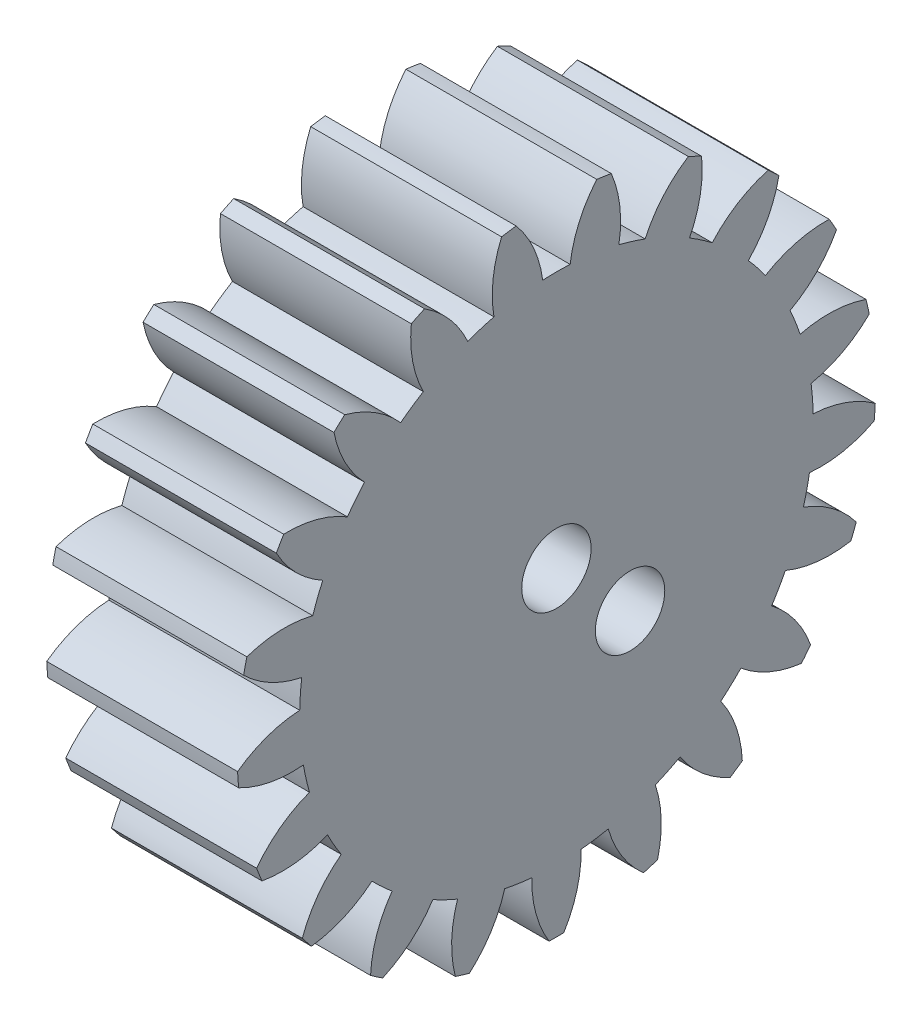
SolidWorks part; units mm, degrees
ref_plane "Plane1" through (0, 0, 0) normal (0, 0, 1) x (1, 0, 0)
ref_plane "Plane2" through (0, 0, 0) normal (0, 1, 0) x (1, 0, 0)
ref_plane "Plane3" through (0, 0, 0) normal (1, 0, 0) x (0, 0, -1)
sketch "HoldingSke" plane through (0, 0, 0) normal (0, 1, 0) x (1, 0, 0)
  line L0 (0, 0) -> (1.167, -0.448)
  line L1 (-15, 0) -> (100, 0) construction
  line L2 (0, 0) -> (-2.1039, 2.3779)
  line L3 (0, 0) -> (-11.863, 4.5341)
  line L4 (0, 0) -> (8.0624, 3.0949)
  line L5 (0, 0) -> (-46.8476, -17.4728)
  line L6 (0, 0) -> (-4.5593, -3.0762)
  line L7 (-2.1039, 2.3779) -> (8.6586, 51.2059)
  line L8 (-76.2, 54.61) -> (-75.9, 54.61)
  line L9 (-71.009, 38.7566) -> (-53.1078, 45.2721)
  line L10 (-76.2, 71.12) -> (104.1128, 71.12)
  line L11 (0, 0) -> (-5.5, 0)
  line L12 (-76.2, 101.6) -> (-76.17, 101.6)
  line L13 (24.9733, 27.94) -> (52.9518, 28.4284)
  line L14 (24.9733, 27.94) -> (24.9743, 27.94)
  line L15 (24.9733, 27.94) -> (100.4006, 29.5858)
  line L16 (-63.627, -0.8) -> (-12.827, -0.8)
  circle A0 centre (0, 0) radius 1
  circle A1 centre (0, 0) radius 7.399
  circle A2 centre (0, 0) radius 37.5
  circle A3 centre (0, 0) radius 1
  dimension "MHD" = 14.798
  dimension "Hub_dia" = 75
  dimension "Bore" = 2
  dimension "MBD" = 2
  dimension "Num_teeth" = 21
  dimension "Pitch" = 1.25
  dimension "Overall_len" = 50
  dimension "Show_teeth" = 21
  dimension "Thickness" = 5.5
  dimension "OAL" = 50.0001
  dimension "T_dim" = 0.3
  dimension "Ap" = 20
  dimension "H" = 19.05
  dimension "Pitch_radius" = 180.3128
  dimension "Width" = 5.5
  dimension "Backlash" = 0.03
  dimension "Addendum_fac" = 1
  dimension "Dedendum_fac" = 1.25
  dimension "Clearance_fac" = 0.25
  dimension "Dedendum_add" = 0.001
  dimension "Module" = 0.8
sketch "BasProSke" plane through (0, 0, 0) normal (0, 1, 0) x (1, 0, 0)
  line L0 (-10, 0) -> (60, 0) construction
  line L1 (0, 0) -> (0, 9.2)
  line L2 (0, 0) -> (5.5, 0)
  line L3 (5.5, 0) -> (5.5, 9.2)
  line L4 (5.5, 9.2) -> (0, 9.2)
  dimension "Thickness" = 5.5
  dimension "Diameter" = 18.4
revolve "Base-Revolve" add sketch "BasProSke" angle 360 about L0
sketch "TooCutSke" plane through (0, 0, 0) normal (1, 0, 0) x (0, 0, -1)
  line L1 (0, 0) -> (0, 107) construction
  line L2 (0, 0) -> (-0.6802, 8.3724) construction
  line L3 (0, 0) -> (-2.498, 16.5734) construction
  line L4 (-0.6802, 8.3724) -> (-1.249, 8.2867) construction
  arc A0 (0.3956, 7.3884) -> (-0.3956, 7.3884) centre (0, 0) ccw
  arc A1 (1.1812, 9.1495) -> (-1.1812, 9.1495) centre (0, 0) ccw
  circle A2 centre (0, 0) radius 8.4 construction
  circle A3 centre (0, 0) radius 7.8934 construction
  arc A4 (-0.3956, 7.3884) -> (-1.1812, 9.1495) centre (-3.7278, 6.9577) ccw
  arc A5 (1.1812, 9.1495) -> (0.3956, 7.3884) centre (3.7278, 6.9577) ccw
  dimension "Root_dia" = 14.798
  dimension "Overcut_dia" = 18.4508
  dimension "Pitch_dia" = 16.8
  dimension "Base_dia" = 15.7868
  dimension "Flank_rad" = 3.36
  dimension "Half_ang" = 8.571
  dimension "Half_CT" = 0.5752
extrude "ToothCut" cut sketch "TooCutSke" along normal through all
fillet "Breaks" [suppressed] radius 0.016
fillet "RootFillets" [suppressed] radius 0.201
pattern_circular "TeethCuts" count 21 every 17.143 about axis through (-10, 0, 0) along (1, 0, 0) of "ToothCut", "RootFillets", "Breaks"
sketch "HubNeaOneSke" plane through (0, 0, 0) normal (-1, 0, 0) x (0, 0, 1)
  circle A0 centre (0, 0) radius 7.399
  dimension "Diameter" = 14.798
extrude "HubNearOne" [suppressed] add sketch "HubNeaOneSke" along normal blind 44.5001
sketch "HubNeaBotSke" plane through (0, 0, 0) normal (-1, 0, 0) x (0, 0, 1)
  circle A0 centre (0, 0) radius 7.399
  dimension "Diameter" = 14.798
extrude "HubNearBoth" [suppressed] add sketch "HubNeaBotSke" along normal blind 22.25
ref_plane "FarPln" through (5.5, 0, 0) normal (1, 0, 0) x (0, 0, -1)
sketch "HubFarSke" plane through (5.5, 0, 0) normal (1, 0, 0) x (0, 0, -1)
  circle A0 centre (0, 0) radius 7.399
  dimension "Diameter" = 14.798
extrude "HubFar" [suppressed] add sketch "HubFarSke" along normal blind 22.25
sketch "BorSke" plane through (0, 0, 0) normal (1, 0, 0) x (0, 0, -1)
  circle A0 centre (0, 0) radius 1
  dimension "Diameter" = 2
extrude "Bore" cut sketch "BorSke" along normal mid plane 100.0001
sketch "KeySke" plane through (0, 0, 0) normal (1, 0, 0) x (0, 0, -1)
  line L0 (-0.4, 0) -> (-0.4, 1.3)
  line L1 (-0.4, 1.3) -> (0.4, 1.3)
  line L2 (0.4, 1.3) -> (0.4, 0)
  line L3 (0, 0) -> (0, 34) construction
  line L4 (-0.4, 0) -> (0.4, 0)
  dimension "Offset" = 1.3
  dimension "Width" = 0.8
extrude "Keyway" [suppressed] cut sketch "KeySke" along normal mid plane 100.0001
pattern_circular "Keyway2" [suppressed] count 2 every 90 about axis through (-10, 0, 0) along (1, 0, 0)
sketch "Sketch1" plane through (5.5, 0, 0) normal (1, 0, 0) x (0, 0, -1)
  line L0 (0, 0) -> (2.1213, -2.1213) construction
  circle A0 centre (2.1213, -2.1213) radius 1
  dimension "D1" = 3
extrude "Cut-Extrude1" cut sketch "Sketch1" against normal blind 5.5 contours A0
equation "' \"Module@HoldingSke\" = 6.35"
equation "' \"Num_teeth@HoldingSke\" = 12"
equation "' \"Ap@HoldingSke\" =  20"
equation "' \"Ap@HoldingSke\" = 20"
equation "' \"Width@HoldingSke\" = 0.5 * 25.4"
equation "' \"Hub_dia@HoldingSke\"= 1 * 25.4"
equation "' \"Hub_dia@HoldingSke\" = 1 * 25.4"
equation "' \"Overall_len@HoldingSke\" = 1.0 * 25.4"
equation "' \"Bore@HoldingSke\" = 0.75 * 25.4"
equation "' \"T_dim@HoldingSke\" = 0.1 * 25.4"
equation "' \"Width@KeySke\" = 0.25 * 25.4"
equation "' \"Show_teeth@HoldingSke\" = 13"
equation "' \"Backlash@HoldingSke\" = 0.009 * 25.4"
equation "' \"Addendum_fac@HoldingSke\" = 1.0"
equation "' \"Dedendum_fac@HoldingSke\" = 1.25"
equation "' \"Dedendum_add@HoldingSke\" = 0.00005 * 25.4"
equation "' \"Clearance_fac@HoldingSke\" = 0.25"
equation "\"Pitch@HoldingSke\" = 1 / \"Module@HoldingSke\""
equation "\"Overcut_dia@TooCutSke\" = (\"Num_teeth@HoldingSke\" + 2 * \"Addendum_fac@HoldingSke\") / \"Pitch@HoldingSke\" + 0.002 * 25.4"
equation "\"Pitch_dia@TooCutSke\" = \"Num_teeth@HoldingSke\" / \"Pitch@HoldingSke\""
equation "\"Base_dia@TooCutSke\" = \"Num_teeth@HoldingSke\" / \"Pitch@HoldingSke\" * cos((\"Ap@HoldingSke\"  * 3.14159265 / 180))"
equation "\"Root_dia@TooCutSke\" = (\"Num_teeth@HoldingSke\" + 2) / \"Pitch@HoldingSke\" - 2 * (\"Addendum_fac@HoldingSke\" + \"Dedendum_fac@HoldingSke\") / \"Pitch@HoldingSke\" - \"Dedendum_add@HoldingSke\" * 2"
equation "\"Half_ang@TooCutSke\" = 180 / \"Num_teeth@HoldingSke\""
equation "\"Half_CT@TooCutSke\" = \"Num_teeth@HoldingSke\" / \"Pitch@HoldingSke\" * sin((3.14159265 / 2 / \"Num_teeth@HoldingSke\")) / 2 - 7 * \"Backlash@HoldingSke\" / 4"
equation "\"Flank_rad@TooCutSke\" = \"Num_teeth@HoldingSke\" / \"Pitch@HoldingSke\" / 5"
equation "\"Radius@RootFillets\" = \"Clearance_fac@HoldingSke\" / \"Pitch@HoldingSke\" + \"Dedendum_add@HoldingSke\""
equation "\"Break_rad@Breaks\" = 0.02 / \"Pitch@HoldingSke\""
equation "\"Thickness@HoldingSke\" = \"Width@HoldingSke\""
equation "\"OAL@HoldingSke\" = \"Thickness@HoldingSke\""
equation "\"MHD@HoldingSke\" = (\"Num_teeth@HoldingSke\" + 2) / \"Pitch@HoldingSke\" - 2 * (\"Addendum_fac@HoldingSke\" + \"Dedendum_fac@HoldingSke\")  / \"Pitch@HoldingSke\" - \"Dedendum_add@HoldingSke\" * 2"
equation "\"MBD@HoldingSke\" = (\"Num_teeth@HoldingSke\" + 2) / \"Pitch@HoldingSke\" - 2 * (\"Addendum_fac@HoldingSke\" + \"Dedendum_fac@HoldingSke\")  / \"Pitch@HoldingSke\" - \"Dedendum_add@HoldingSke\" * 2 - 0.002 * 25.4"
equation "\"MHD@HoldingSke\" = ((sgn( \"MHD@HoldingSke\" - \"Hub_dia@HoldingSke\" )-1)*( \"MHD@HoldingSke\" - \"Hub_dia@HoldingSke\" ))/-2+ \"Hub_dia@HoldingSke\""
equation "\"MBD@HoldingSke\" = ((sgn( \"MBD@HoldingSke\" - \"Bore@HoldingSke\" )-1)*( \"MBD@HoldingSke\" - \"Bore@HoldingSke\" ))/-2+ \"Bore@HoldingSke\""
equation "\"OAL@HoldingSke\" = ((sgn( \"OAL@HoldingSke\" - \"Overall_len@HoldingSke\" )+1)*( \"OAL@HoldingSke\" - \"Overall_len@HoldingSke\" ))/2 + \"Overall_len@HoldingSke\" + 0.000002 * 25.4"
equation "\"Num_teeth@TeethCuts\" = int( \"Show_teeth@HoldingSke\" ) + 1"
equation "\"Num_teeth@TeethCuts\" = ((sgn( \"Num_teeth@TeethCuts\" - \"Num_teeth@HoldingSke\" )-1)*( \"Num_teeth@TeethCuts\" - \"Num_teeth@HoldingSke\" ))/-2+ \"Num_teeth@HoldingSke\""
equation "\"Num_teeth@TeethCuts\" = ((sgn( \"Num_teeth@TeethCuts\" - 2.0)+1)*( \"Num_teeth@TeethCuts\" - 2.0))/2 +2.0"
equation "\"Angle@TeethCuts\" = 360.0 / \"Num_teeth@HoldingSke\""
equation "\"Diameter@BasProSke\" = (\"Num_teeth@HoldingSke\" + 2 * \"Addendum_fac@HoldingSke\") / \"Pitch@HoldingSke\""
equation "\"Thickness@BasProSke\"  = \"Thickness@HoldingSke\""
equation "' \"Fillet_rad@BasProSke\" =  \"Thickness@HoldingSke\" * 0.05"
equation "' \"Fillet_rad@BasProSke\" = \"Thickness@HoldingSke\" * 0.05"
equation "\"MHD@HoldingSke\" = ((sgn( \"MHD@HoldingSke\" - \"Root_dia@TooCutSke\" )-1)*( \"MHD@HoldingSke\" - \"Root_dia@TooCutSke\" ))/-2+ \"Root_dia@TooCutSke\""
equation "\"Diameter@HubNeaOneSke\" = \"MHD@HoldingSke\""
equation "\"Length@HubNearOne\" = \"OAL@HoldingSke\" - \"Thickness@BasProSke\""
equation "\"Diameter@HubNeaBotSke\" = \"MHD@HoldingSke\""
equation "\"Length@HubNearBoth\" = ( \"OAL@HoldingSke\" - \"Thickness@BasProSke\" ) / 2.0"
equation "\"Thickness@FarPln\" = \"Thickness@BasProSke\""
equation "\"Diameter@HubFarSke\" = \"MHD@HoldingSke\""
equation "\"Length@HubFar\" = ( \"OAL@HoldingSke\" - \"Thickness@BasProSke\" ) / 2.0"
equation "\"Diameter@BorSke\" = \"MBD@HoldingSke\""
equation "\"D1@Bore\" = \"OAL@HoldingSke\" * 2.0"
equation "\"D1@Keyway\" = \"OAL@HoldingSke\" * 2.0"
equation "\"Offset@KeySke\" = \"T_dim@HoldingSke\" + \"MBD@HoldingSke\" / 2.0"
